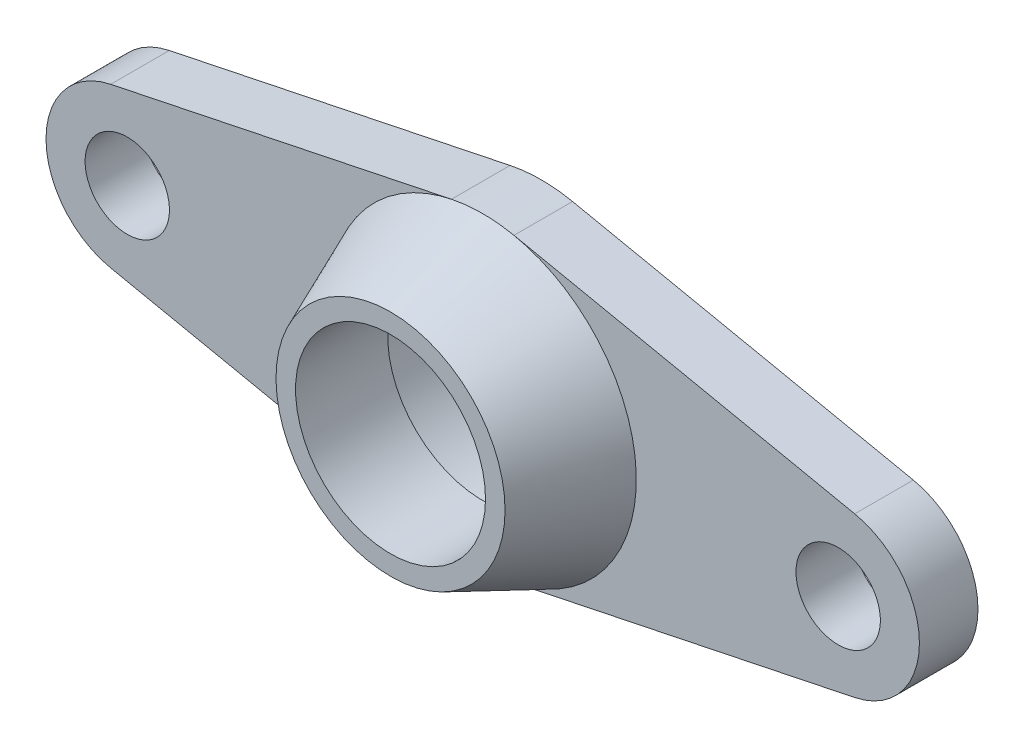
SolidWorks part; units mm, degrees
ref_plane "Front Plane" through (0, 0, 0) normal (0, 0, 1) x (1, 0, 0)
ref_plane "Top Plane" through (0, 0, 0) normal (0, 1, 0) x (1, 0, 0)
ref_plane "Right Plane" through (0, 0, 0) normal (1, 0, 0) x (0, 0, -1)
sketch "Sketch1" plane through (0, 0, 0) normal (0, 0, 1) x (1, 0, 0)
  line L0 (-30.2385, 6.4658) -> (-2.5405, 12.2229)
  line L1 (-30.2385, -6.4658) -> (-2.5405, -12.2229)
  line L3 (2.5405, -12.2229) -> (30.2385, -6.4658)
  line L4 (2.5405, 12.2229) -> (30.2385, 6.4658)
  circle A0 centre (0, 0) radius 6.1341
  circle A1 centre (-28.8946, 0) radius 3.429
  circle A2 centre (28.8946, 0) radius 3.429
  circle A3 centre (0, 0) radius 9.3091
  circle A4 centre (-28.8946, 0) radius 6.604
  circle A5 centre (28.8946, 0) radius 6.604
  circle A6 centre (0, 0) radius 12.4841
  point P13 (2.895, 12.2231)
  point P18 (-2.8017, 10.843)
  point P20 (41.9056, -12.4842)
  point P21 (36.0289, 8.8603)
  point P23 (2.2362, 10.843)
  point P24 (-3.2644, -10.7998)
  point P25 (3.7785, -10.7998)
  point P28 (-5.2179, 14.3387)
  point P29 (-4.1383, -15.2208)
  point P30 (6.4517, -15.2208)
  point P31 (3.3158, 14.8014)
  point P32 (1.2158, 13.0033)
  point P33 (-3.4251, 13.4624)
  point P34 (2.1486, -13.1971)
  dimension "D1" = 12.2682
  dimension "D2" = 6.858
  dimension "D3" = 28.8946
  dimension "D4" = 28.8946
  dimension "D5" = 3.175
  dimension "D6" = 3.175
  dimension "D7" = 3.175
  dimension "D8" = 3.175
extrude "Boss-Extrude1" add sketch "Sketch1" along normal blind 4.7625 contours A4 A1 | A6 L0 A4 L1 | A6 A3 | A6 L3 A5 L4 | A5 A2
ref_plane "Plane1" through (0, 0, 12.2555) normal (0, 0, 1) x (1, 0, 0)
sketch "Sketch2" plane through (0, 0, 12.2555) normal (0, 0, 1) x (1, 0, 0)
  circle A0 centre (0, 0) radius 9.3091 construction
  circle A1 centre (0, 0) radius 9.3091
  circle A2 centre (0, 0) radius 7.7216
  point P4 (0, 0)
  dimension "D1" = 1.5875
sketch "Sketch3" plane through (0, 0, 4.7625) normal (0, 0, 1) x (1, 0, 0)
  circle A1 centre (0, 0) radius 9.3091 construction
  circle A2 centre (0, 0) radius 12.4841
  circle A3 centre (0, 0) radius 12.4841
  circle A4 centre (0, 0) radius 9.3091
  dimension "D1" = 3.175
sketch "Sketch4" plane through (0, 0, 0) normal (1, 0, 0) x (0, 0, -1)
  line L1 (-4.7625, 12.4841) -> (-4.7625, -12.4841) construction
  line L2 (-12.2555, 0) -> (-4.7625, 0) construction
  line L3 (-12.2555, 9.3091) -> (-12.2555, -9.3091) construction
  point P0 (-12.2555, 0)
  point P2 (0, 0)
loft "Loft3" add section "Sketch3" section "Sketch2"
sketch "Sketch5" plane through (0, 0, 12.2555) normal (0, 0, 1) x (1, 0, 0)
  circle A0 centre (0, 0) radius 7.7216 construction
  circle A1 centre (0, 0) radius 7.7216
extrude "Cut-Extrude1" cut sketch "Sketch5" against normal through all
